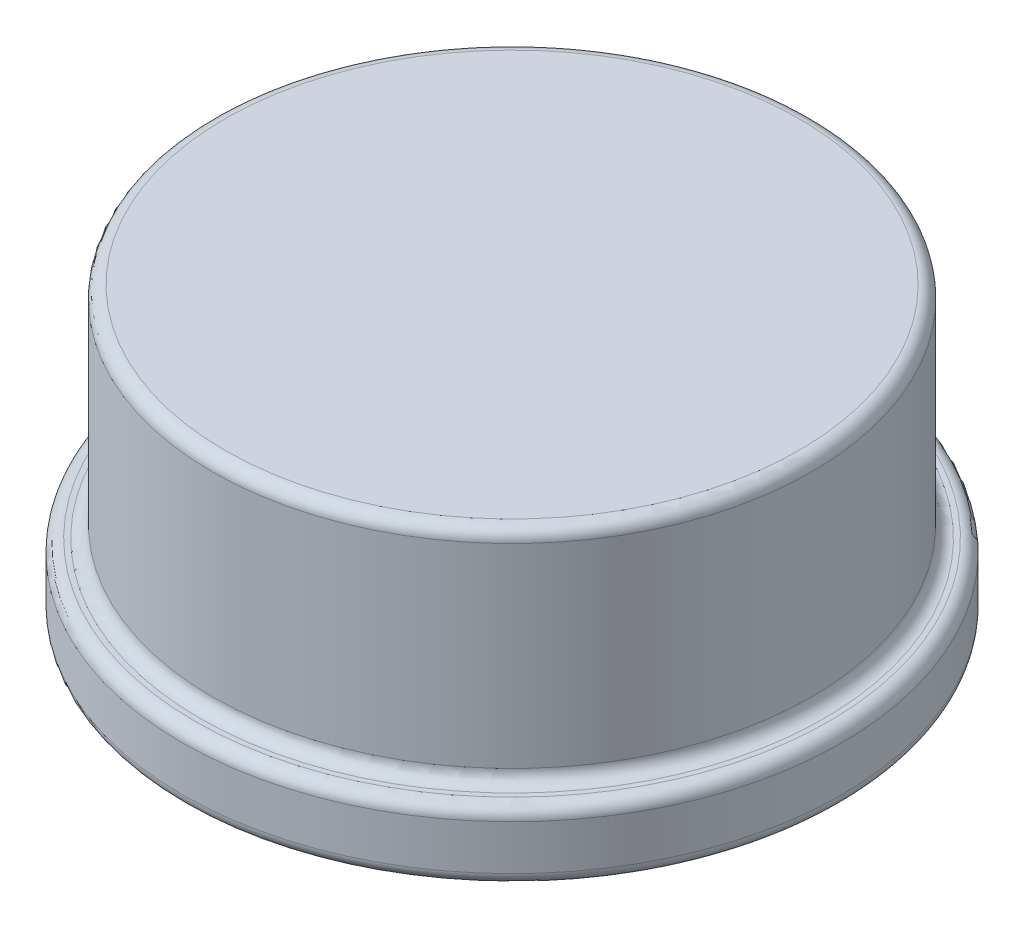
SolidWorks part; units mm, degrees
ref_plane "Front Plane" through (0, 0, 0) normal (0, 0, 1) x (1, 0, 0)
ref_plane "Top Plane" through (0, 0, 0) normal (0, 1, 0) x (1, 0, 0)
ref_plane "Right Plane" through (0, 0, 0) normal (1, 0, 0) x (0, 0, -1)
sketch "Sketch1" plane through (0, 0, 0) normal (1, 0, 0) x (0, 0, -1)
  line L0 (0, 13.8679) -> (0, -14.7736) construction
  line L1 (0, 2.0642) -> (-5.75, 2.0642)
  line L2 (-6, 1.8142) -> (-6, -2.0858)
  line L3 (-6.25, -2.3358) -> (-6.35, -2.3358)
  line L4 (-6.6, -2.5858) -> (-6.6, -3.4858)
  line L5 (0, 1.0642) -> (-4.75, 1.0642)
  line L6 (-5, 0.8142) -> (-5, -3.4858)
  line L7 (-5.25, -3.7358) -> (-6.35, -3.7358)
  line L8 (0, 2.0642) -> (0, 1.0642)
  arc A0 (-5, -3.4858) -> (-5.25, -3.7358) centre (-5.25, -3.4858) cw
  arc A1 (-6.6, -3.4858) -> (-6.35, -3.7358) centre (-6.35, -3.4858) ccw
  arc A2 (-6.6, -2.5858) -> (-6.35, -2.3358) centre (-6.35, -2.5858) cw
  arc A3 (-6.25, -2.3358) -> (-6, -2.0858) centre (-6.25, -2.0858) ccw
  arc A4 (-5, 0.8142) -> (-4.75, 1.0642) centre (-4.75, 0.8142) cw
  arc A5 (-6, 1.8142) -> (-5.75, 2.0642) centre (-5.75, 1.8142) cw
  point P19 (-6, -2.3358)
  point P24 (-6, 2.0642)
  dimension "D6" = 0.25
  dimension "D1" = 12
  dimension "D2" = 10
  dimension "D3" = 1
  dimension "D4" = 13.2
  dimension "D5" = 4.4
revolve "Revolve1" add sketch "Sketch1" angle 360 about L0
